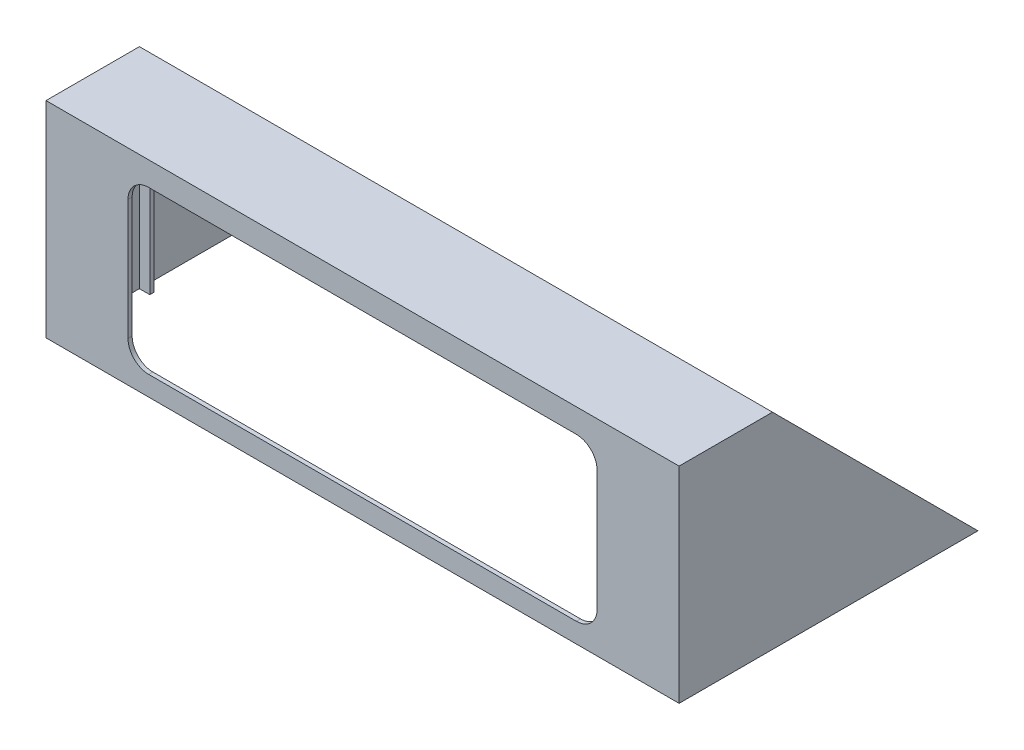
SolidWorks part; units mm, degrees
ref_plane "Front Plane" through (0, 0, 0) normal (0, 0, 1) x (1, 0, 0)
ref_plane "Top Plane" through (0, 0, 0) normal (0, 1, 0) x (1, 0, 0)
ref_plane "Right Plane" through (0, 0, 0) normal (1, 0, 0) x (0, 0, -1)
sketch "Sketch1" plane through (0, 0, 0) normal (0, 0, 1) x (1, 0, 0)
  line L1 (75.25, -24.25) -> (-75.25, -24.25)
  line L2 (75.25, -24.25) -> (75.25, 24.25)
  line L3 (75.25, 24.25) -> (-75.25, 24.25)
  line L4 (-75.25, -24.25) -> (-75.25, 24.25)
  line L5 (75.25, -24.25) -> (-75.25, 24.25) construction
  line L6 (75.25, 24.25) -> (-75.25, -24.25) construction
  point P0 (0, 0)
  dimension "D1" = 150.5
  dimension "D2" = 48.5
extrude "Boss-Extrude1" add sketch "Sketch1" along normal mid plane 20.5
shell "Shell1" thickness 1
sketch "Sketch2" plane through (0, 0, -11.25) normal (0, 0, -1) x (-1, 0, 0)
  line L0 (76.25, -24.25) -> (-76.25, -24.25) construction
  line L1 (-72.75, -24.25) -> (72.75, -24.25)
  line L2 (-72.75, -24.25) -> (-72.75, 24.25)
  line L3 (-72.75, 24.25) -> (72.75, 24.25)
  line L4 (72.75, -24.25) -> (72.75, 24.25)
  line L6 (-76.25, -24.25) -> (-76.25, 25.25) construction
  line L7 (76.25, 25.25) -> (76.25, -24.25) construction
  line L8 (-76.25, 25.25) -> (76.25, 25.25) construction
  dimension "D1" = 3.5
  dimension "D2" = 3.5
  dimension "D3" = 1
extrude "Cut-Extrude1" cut sketch "Sketch2" against normal up to surface (1 mm away) up to face at (0, 0, -10.25)
sketch "Sketch3" plane through (0, 0, 11.25) normal (0, 0, 1) x (1, 0, 0)
  line L1 (51.5, -19.5) -> (-51.5, -19.5)
  line L2 (56.5, -14.5) -> (56.5, 14.5)
  line L3 (51.5, 19.5) -> (-51.5, 19.5)
  line L4 (-56.5, -14.5) -> (-56.5, 14.5)
  line L5 (56.5, -19.5) -> (-56.5, 19.5) construction
  line L6 (56.5, 19.5) -> (-56.5, -19.5) construction
  arc A0 (51.5, -19.5) -> (56.5, -14.5) centre (51.5, -14.5) ccw
  arc A1 (-51.5, -19.5) -> (-56.5, -14.5) centre (-51.5, -14.5) cw
  arc A2 (56.5, 14.5) -> (51.5, 19.5) centre (51.5, 14.5) ccw
  arc A3 (-51.5, 19.5) -> (-56.5, 14.5) centre (-51.5, 14.5) ccw
  point P0 (0, 0)
  dimension "D3" = 5
  dimension "D1" = 113
  dimension "D2" = 39
extrude "Cut-Extrude2" cut sketch "Sketch3" against normal up to surface (1 mm away) up to face at (0, 0, 10.25)
sketch "Sketch4" plane through (76.25, 0, 0) normal (1, 0, 0) x (0, 0, -1)
  line L0 (11.25, 25.25) -> (60.75, -24.25)
  line L1 (60.75, -24.25) -> (11.25, -24.25)
  line L2 (11.25, 25.25) -> (11.25, -24.25)
  dimension "D1" = 45
extrude "Boss-Extrude2" add sketch "Sketch4" against normal blind 1 contours L0 L1 L2
mirror "Mirror1" about plane through (0, 0, 0) normal (1, 0, 0) of "Boss-Extrude2"
